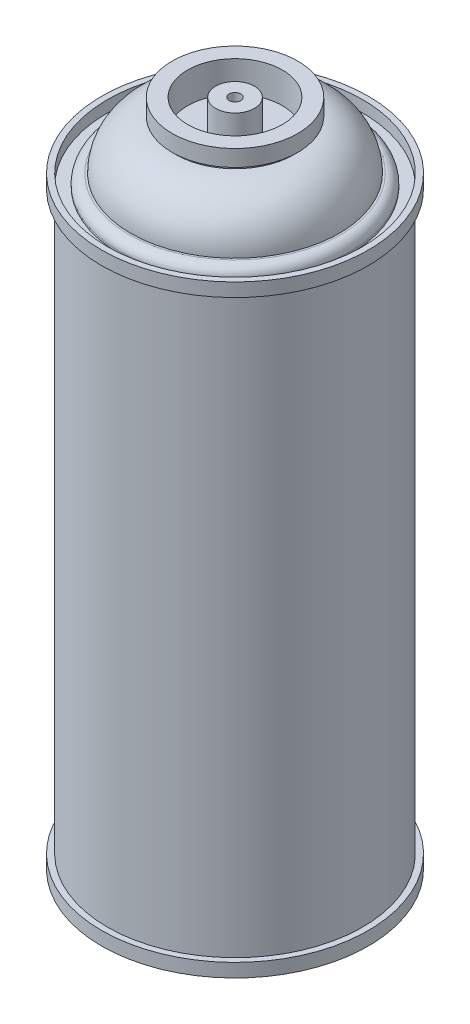
SolidWorks part; units mm, degrees
ref_plane "Front" through (0, 0, 0) normal (0, 0, 1) x (1, 0, 0)
ref_plane "Top" through (0, 0, 0) normal (0, 1, 0) x (1, 0, 0)
ref_plane "Right" through (0, 0, 0) normal (1, 0, 0) x (0, 0, -1)
sketch "Sketch1" plane through (0, 0, 0) normal (0, 1, 0) x (1, 0, 0)
  circle A0 centre (0, 0) radius 33
  dimension "D1" = 66
extrude "Boss-Extrude1" add sketch "Sketch1" along normal blind 156
sketch "Sketch2" plane through (0, 0, 0) normal (1, 0, 0) x (0, 0, -1)
  line L0 (33, 156) -> (27, 156) construction
  line L1 (33, 156) -> (-33, 156) construction
  line L2 (15.25, 167.75) -> (15.25, 168.75)
  line L3 (15.25, 168.75) -> (16.25, 168.75)
  line L4 (16.25, 168.75) -> (16.25, 173)
  line L5 (16.25, 173) -> (12.25, 173)
  line L6 (12.25, 173) -> (12.25, 165)
  line L7 (12.25, 165) -> (5, 165)
  line L8 (5, 165) -> (5, 173)
  line L9 (5, 173) -> (0, 173)
  line L10 (0, 173) -> (0, 156)
  line L11 (27, 156) -> (0, 156)
  arc A0 (27, 156) -> (15.25, 167.75) centre (15.25, 156) ccw
  dimension "D1" = 17
  dimension "D2" = 6
  dimension "D3" = 16.25
  dimension "D4" = 4
  dimension "D5" = 5
  dimension "D6" = 8
  dimension "D7" = 1
revolve "Revolve1" add sketch "Sketch2" angle 360 about L10
sketch "Sketch3" plane through (0, 156, 0) normal (0, 1, 0) x (1, 0, 0)
  circle A0 centre (0, 0) radius 34.5
  dimension "D1" = 69
extrude "Boss-Extrude2" add sketch "Sketch3" against normal blind 3.5
pattern_linear "LPattern1" count 2 spacing 152.5 along (0, -1, 0) of "Boss-Extrude2"
sketch "Sketch5" plane through (0, 0, 0) normal (0, 0, 1) x (1, 0, 0)
  line L0 (0, 0) -> (-32.5, 0)
  line L1 (-34.5, 0) -> (34.5, 0) construction
  line L2 (0, 12) -> (0, 0)
  arc A0 (-32.5, 0) -> (0, 12) centre (0, -38.0104) cw
  dimension "D1" = 12
  dimension "D2" = 2
revolve "Cut-Revolve1" cut sketch "Sketch5" angle 360 about L2
sketch "Sketch6" plane through (0, 173, 0) normal (0, 1, 0) x (1, 0, 0)
  circle A0 centre (0, 0) radius 1.5
  dimension "D1" = 3
extrude "Cut-Extrude1" cut sketch "Sketch6" against normal blind 6
sketch "Sketch7" plane through (0, 156, 0) normal (0, 1, 0) x (1, 0, 0)
  circle A0 centre (0, 0) radius 33
  circle A1 centre (0, 0) radius 30
  circle A2 centre (0, 0) radius 34.5 construction
  dimension "D1" = 1.5
  dimension "D2" = 3
extrude "Cut-Extrude2" cut sketch "Sketch7" against normal blind 3
fillet "Fillet1" radius 2.5 1 edges at (0, 156, 30)
